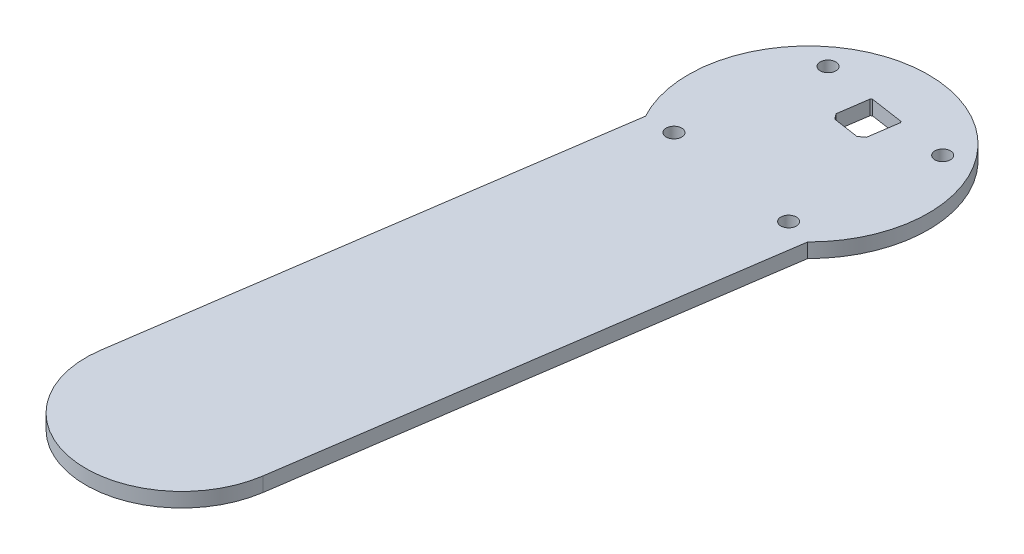
SolidWorks part; units mm, degrees
ref_plane "前视基准面" through (0, 0, 0) normal (0, 0, 1) x (1, 0, 0)
ref_plane "上视基准面" through (0, 0, 0) normal (0, 1, 0) x (1, 0, 0)
ref_plane "右视基准面" through (0, 0, 0) normal (1, 0, 0) x (0, 0, -1)
sketch "草图1" plane through (0, 0, 0) normal (0, 1, 0) x (1, 0, 0)
  line L2 (-43.9337, -23.8711) -> (-72.987, -221.7496)
  line L4 (6.1644, -233.3709) -> (35.2177, -35.4924)
  arc A0 (35.2177, -35.4924) -> (-43.9337, -23.8711) centre (0, 0) ccw
  arc A1 (-72.987, -221.7496) -> (6.1644, -233.3709) centre (-33.4113, -227.5603) ccw
  point P10 (-4.358, -29.6818)
  dimension "D1" = 100
  dimension "D5" = 40
  dimension "D2" = 40
  dimension "D3" = 200
  dimension "D4" = 80
  dimension "D6" = 40
  dimension "D7" = 197.8785
  dimension "D8" = 40
extrude "凸台-拉伸1" add sketch "草图1" along normal blind 6
sketch "草图6" plane through (0, 0, 0) normal (0, -1, 0) x (1, 0, 0)
  circle A0 centre (-32.093, 23.8755) radius 3.25
  circle A1 centre (23.8755, 32.093) radius 3.25
  circle A2 centre (32.093, -23.8755) radius 3.25
  circle A3 centre (-23.8755, -32.093) radius 3.25
  dimension "D1" = 6.5
  dimension "D2" = 6.5
  dimension "D3" = 6.5
  dimension "D4" = 6.5
extrude "切除-拉伸3" cut sketch "草图6" against normal blind 28
sketch "草图11" plane through (0, 6, 0) normal (0, 1, 0) x (1, 0, 0)
  line L0 (9.7134, 14.5273) -> (11.5292, 26.8948)
  line L1 (11.5292, 26.8948) -> (11.1071, 27.4621)
  line L2 (11.1071, 27.4621) -> (-2.7444, 29.4958)
  line L3 (-2.7444, 29.4958) -> (-3.3117, 29.0737)
  line L4 (-3.3117, 29.0737) -> (-5.1275, 16.7063)
  line L5 (-5.1275, 16.7063) -> (-3.4393, 14.437)
  line L6 (-3.4393, 14.437) -> (7.4441, 12.8391)
  line L7 (7.4441, 12.8391) -> (9.7134, 14.5273)
extrude "切除-拉伸11" cut sketch "草图11" against normal blind 35
